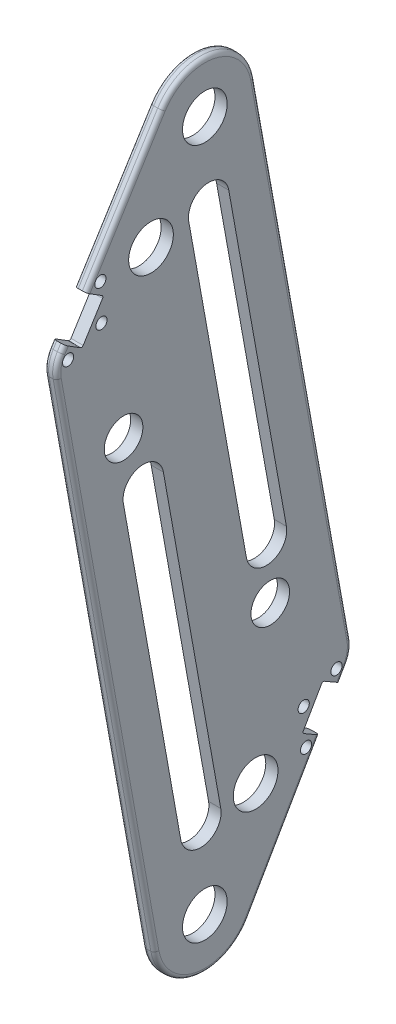
SolidWorks part; units mm, degrees
material "6061 合金"
ref_plane "前视基准面" through (0, 0, 0) normal (0, 0, 1) x (1, 0, 0)
ref_plane "上视基准面" through (0, 0, 0) normal (0, 1, 0) x (1, 0, 0)
ref_plane "右视基准面" through (0, 0, 0) normal (1, 0, 0) x (0, 0, -1)
other "Configuration Table"
sketch "草图1" plane through (0, 0, 0) normal (1, 0, 0) x (0, 0, -1)
  line L0 (0, 0) -> (40, -222)
  line L1 (40, -222) -> (-25, -43.3013)
  line L2 (-25, -43.3013) -> (0, 0)
  line L3 (0, 0) -> (0, -340) construction
  line L4 (0, -340) -> (25, -296.6987)
  line L5 (25, -296.6987) -> (-40, -117)
  line L6 (-40, -117) -> (0, -340)
  line L8 (0, -340) -> (-40, -340)
  line L11 (-40, -340) -> (-40, -117)
  circle A0 centre (0, 0) radius 11
  circle A1 centre (-25, -43.3013) radius 11
  circle A2 centre (25, -296.6987) radius 11
  circle A3 centre (0, -340) radius 11
  circle A4 centre (40, -222) radius 9.5
  circle A5 centre (-40, -117) radius 9.5
  circle A6 centre (-25, -43.3013) radius 14
  circle A7 centre (-40, -117) radius 11.5
  dimension "D7" = 22
  dimension "D8" = 19
  dimension "D9" = 28
  dimension "D10" = 23
  dimension "D1" = 50
  dimension "D2" = 40
  dimension "D3" = 222
  dimension "D4" = 40
  dimension "D5" = 340
  dimension "D6" = 223
  dimension "D11" = 30
  dimension "D12" = 30
sketch "草图2" plane through (0, 0, 0) normal (1, 0, 0) x (0, 0, -1)
  line L0 (13.1193, 68.1722) -> (-73.6936, -70.7575)
  line L2 (-73.6936, -70.7575) -> (-12.5358, -411.7126)
  line L3 (-12.5358, -411.7126) -> (72.9169, -263.7043)
  line L4 (72.9169, -263.7043) -> (13.1193, 68.1722)
  line L5 (-40, -117) -> (0, -340) construction
  line L6 (0, 0) -> (40, -222) construction
  line L7 (0, -340) -> (25, -296.6987) construction
  line L8 (0, -340) -> (25, -296.6987) construction
  line L9 (0, 0) -> (-26.496, -42.4024) construction
  line L10 (45.4645, -406.4097) -> (120.1455, -406.4097) construction
  line L11 (0, 0) -> (32.2, -223.3) construction
  circle A0 centre (-40, -117) radius 9.5 construction
  circle A2 centre (0, -340) radius 11 construction
  circle A5 centre (0, 0) radius 11 construction
  circle A6 centre (-40, -117) radius 9.5
  circle A7 centre (25, -296.6987) radius 11
  circle A8 centre (0, -340) radius 11
  circle A9 centre (-26.496, -42.4024) radius 11
  circle A10 centre (32.2, -223.3) radius 9.5
  circle A11 centre (0, 0) radius 11
  dimension "D5" = 22
  dimension "D9" = 22
  dimension "D13" = 19
  dimension "D1" = 50
  dimension "D2" = 25
  dimension "D3" = 25
  dimension "D4" = 25
  dimension "D6" = 60
  dimension "D7" = 25
  dimension "D8" = 58
  dimension "D10" = 50
  dimension "D11" = 223.3
  dimension "D12" = 32.2
extrude "凸台-拉伸1" add sketch "草图2" along normal blind 6
sketch "草图3" plane through (6, 0, 0) normal (1, 0, 0) x (0, 0, -1)
  line L3 (-73.6936, -70.7575) -> (-12.5358, -411.7126) construction
  line L5 (72.9169, -263.7043) -> (13.1193, 68.1722) construction
  line L8 (-12.5358, -411.7126) -> (72.9169, -263.7043) construction
  line L12 (-30.2487, -143.0438) -> (-2, -300.5304) construction
  line L13 (-20.4058, -141.2783) -> (7.843, -298.7648)
  line L14 (-40.0916, -144.8094) -> (-11.8429, -302.2959)
  line L15 (-40, -117) -> (0, -340) construction
  line L16 (-16.1243, -221.7871) -> (-20, -228.5) construction
  line L18 (1.9419, -38.9745) -> (30.3139, -196.4389) construction
  line L19 (11.7834, -37.2012) -> (40.1554, -194.6656)
  line L20 (-7.8996, -40.7477) -> (20.4724, -198.2121)
  line L21 (16.1279, -117.7067) -> (20, -111) construction
  arc A4 (-20.4058, -141.2783) -> (-40.0916, -144.8094) centre (-30.2487, -143.0438) ccw
  arc A5 (-11.8429, -302.2959) -> (7.843, -298.7648) centre (-2, -300.5304) ccw
  arc A6 (11.7834, -37.2012) -> (-7.8996, -40.7477) centre (1.9419, -38.9745) ccw
  arc A7 (20.4724, -198.2121) -> (40.1554, -194.6656) centre (30.3139, -196.4389) ccw
  point P30 (-16.1243, -221.7871)
  point P47 (16.1279, -117.7067)
  dimension "D7" = 10
  dimension "D9" = 10
  dimension "D5" = 160
  dimension "D6" = 30
  dimension "D8" = 160
  dimension "D10" = 30
extrude "切除-拉伸1" cut sketch "草图3" against normal blind 10
fillet "圆角1" radius 25 2 edges at (3, -411.7126, 12.5358) (3, 68.1722, -13.1193)
sketch "草图4" plane through (6, 0, 0) normal (1, 0, 0) x (0, 0, -1)
  line L0 (-68.8939, -63.0763) -> (-58.2956, -46.1154)
  line L1 (-68.8939, -63.0763) -> (-60.4135, -68.3755)
  line L2 (-58.2956, -46.1154) -> (-49.8151, -51.4146)
  line L3 (-60.4135, -68.3755) -> (-49.8151, -51.4146)
  line L4 (-21.2012, 13.248) -> (-73.6936, -70.7575) construction
  line L5 (-63.5947, -54.5959) -> (-50.874, -62.5447) construction
  line L6 (-51.4057, -44.5247) -> (-67.3033, -69.9662) construction
  line L7 (-63.5947, -54.5959) -> (-55.1143, -59.8951) construction
  line L8 (61.6506, -283.218) -> (52.9904, -278.218) construction
  line L9 (21.6506, -352.5) -> (72.9169, -263.7043) construction
  line L10 (64.8205, -267.7276) -> (49.8205, -293.7083) construction
  line L11 (61.6506, -283.218) -> (48.6603, -275.718) construction
  line L12 (47.9904, -286.8782) -> (57.9904, -269.5577)
  line L13 (66.6506, -274.5577) -> (57.9904, -269.5577)
  line L14 (56.6506, -291.8782) -> (47.9904, -286.8782)
  line L15 (56.6506, -291.8782) -> (66.6506, -274.5577)
  line L16 (-63.5947, -54.5959) -> (-55.1143, -59.8951) construction
  circle A0 centre (-26.496, -42.4024) radius 20 construction
  circle A1 centre (-51.4057, -44.5247) radius 2.75
  circle A2 centre (-67.3033, -69.9662) radius 2.75
  circle A3 centre (-50.874, -62.5447) radius 2.75
  circle A4 centre (25, -296.6987) radius 20 construction
  circle A5 centre (48.6603, -275.718) radius 2.75
  circle A6 centre (49.8205, -293.7083) radius 2.75
  circle A7 centre (64.8205, -267.7276) radius 2.75
  point P16 (-59.3545, -57.2455)
  point P37 (57.3205, -280.718)
  dimension "D3" = 40
  dimension "D6" = 5.5
  dimension "D7" = 20
  dimension "D11" = 5.5
  dimension "D1" = 20
  dimension "D2" = 10
  dimension "D4" = 15
  dimension "D5" = 30
  dimension "D8" = 10
  dimension "D9" = 30
  dimension "D10" = 15
extrude "切除-拉伸2" cut sketch "草图4" against normal blind 10
fillet "圆角2" radius 15 2 edges at (3, -70.7575, 73.6936) (3, -263.7043, -72.9169)
fillet "圆角3" radius 1 4 edges at (3, -68.3755, 60.4135) (3, -51.4146, 49.8151) (3, -286.8782, -47.9904) (3, -269.5577, -57.9904)
sketch "草图5" plane through (6, 0, 0) normal (1, 0, 0) x (0, 0, -1)
  line L0 (0, 0) -> (0, -340) construction
fillet "圆角4" radius 2 20 edges at (6, -64.4646, 69.7614) (6, -70.9613, 72.6368) (6, -210.4319, 48.6399) (6, -364.6266, 4.3049) (0, -64.4646, 69.7614) (0, -70.9613, 72.6368) (0, -210.4319, 48.6399) (0, -364.6266, 4.3049) (0, -271.5088, -68.4109) (0, -263.537, -71.9578) (0, -16.4337, 39.7484) (0, 24.5495, -4.7244) (6, -271.5088, -68.4109) (6, -263.537, -71.9578) (6, -16.4337, 39.7484) (6, 24.5495, -4.7244) (6, -322.1891, -39.1506) (0, -322.1891, -39.1506) (0, -126.9335, -48.2735) (6, -126.9335, -48.2735)
ref_plane "基准面1" through (0, 0, 0) normal (0, 0, 1) x (0, -1, 0)
